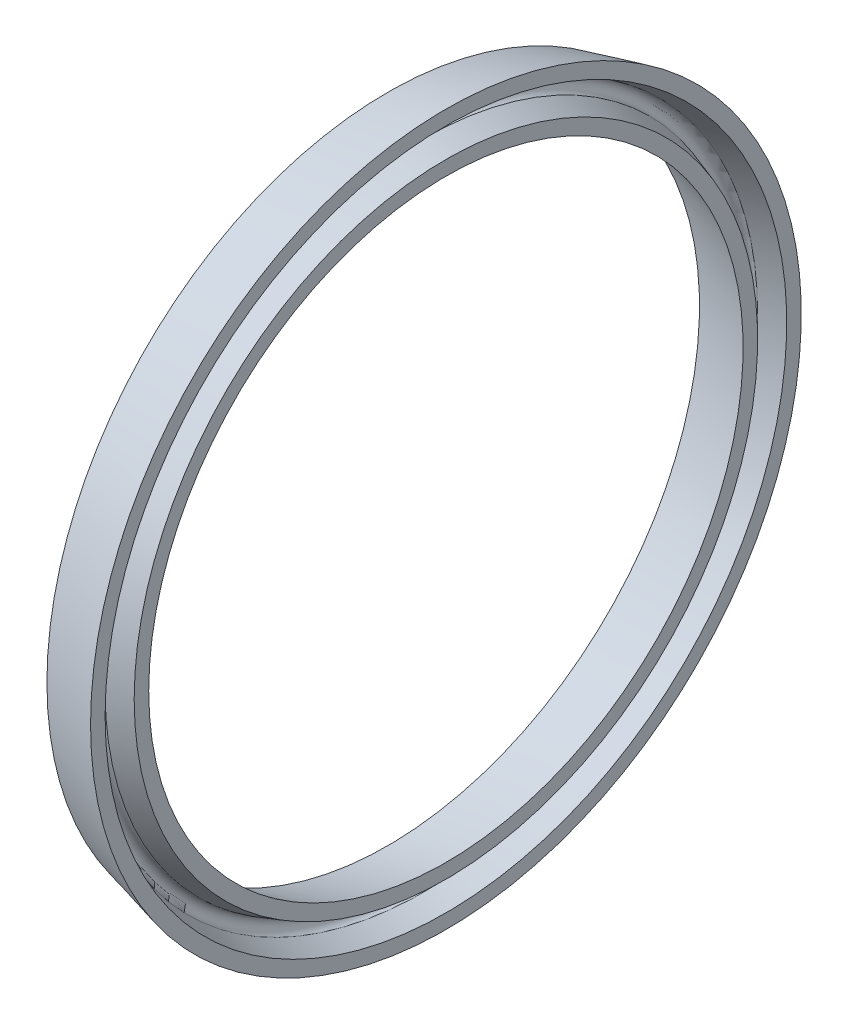
SolidWorks part; units mm, degrees
ref_plane "Front Plane" through (0, 0, 0) normal (0, 0, 1) x (1, 0, 0)
ref_plane "Top Plane" through (0, 0, 0) normal (0, 1, 0) x (1, 0, 0)
ref_plane "Right Plane" through (0, 0, 0) normal (1, 0, 0) x (0, 0, -1)
sketch "Sketch1" plane through (0, 0, 0) normal (0, 0, 1) x (1, 0, 0)
  line L0 (0, 0) -> (408325.3941, 0) construction
  line L1 (0, 0) -> (0, -408325.3941) construction
  line L2 (0, 73.31) -> (-12, 70.31)
  line L3 (-12, 70.31) -> (-12, 64.31)
  line L4 (-12, 64.31) -> (0, 61.31)
  line L5 (0, 61.31) -> (0, 64.31)
  line L8 (0, 70.31) -> (0, 73.31)
  line L9 (0, 70.31) -> (-4.5, 68.81)
  line L10 (0, 64.31) -> (-4.5, 65.81)
  line L11 (-12, 67.31) -> (0, 67.31) construction
  arc A2 (-4.5, 68.81) -> (-4.5, 65.81) centre (-4.5, 67.31) ccw
  point P13 (-12, 67.31)
  point P14 (-6, 67.31)
  point P18 (-4.7068, 67.31)
  point P21 (0, 0)
  point P22 (-4.7068, 66.0168)
  point P23 (-4.7068, 68.6032)
  point P24 (0, 64.31)
  point P25 (0, 0)
  point P26 (-4.7068, 68.6032)
  point P27 (-4.7068, 66.0168)
  point P28 (0, 64.31)
  dimension "D9" = 1.5
  dimension "D1" = 146.62
  dimension "D2" = 140.62
  dimension "D3" = 12
  dimension "D4" = 6
  dimension "D5" = 12
  dimension "D6" = 3
  dimension "D7" = 3
  dimension "D8" = 6
revolve "Revolve1" add sketch "Sketch1" angle 360 about L0
